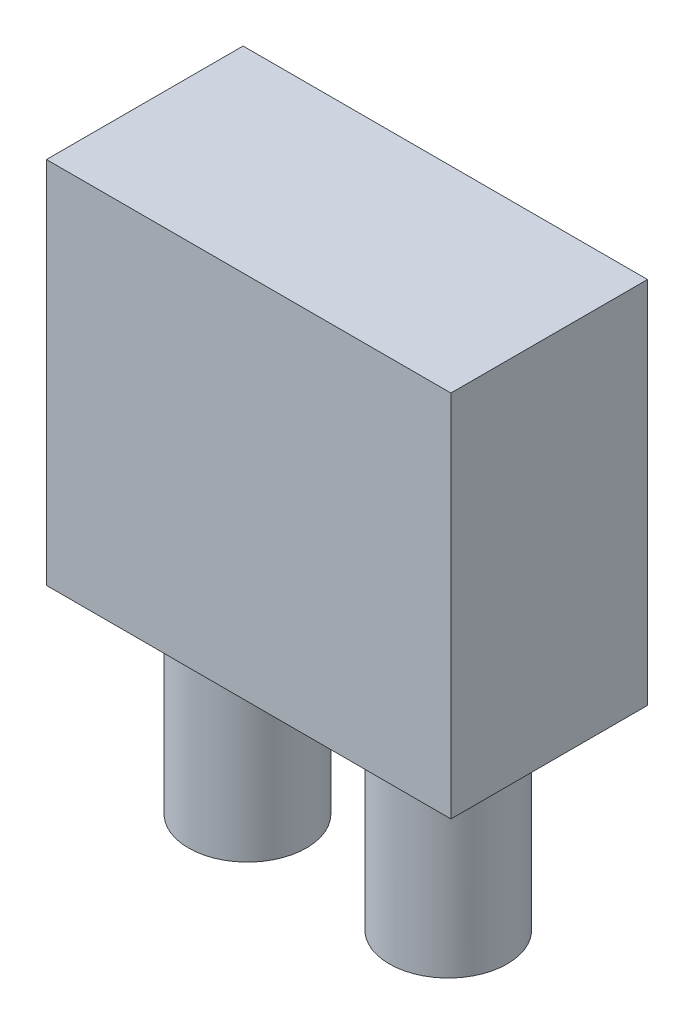
SolidWorks part; units mm, degrees
ref_plane "前视基准面" through (0, 0, 0) normal (0, 0, 1) x (1, 0, 0)
ref_plane "上视基准面" through (0, 0, 0) normal (0, 1, 0) x (1, 0, 0)
ref_plane "右视基准面" through (0, 0, 0) normal (1, 0, 0) x (0, 0, -1)
sketch "草图1" plane through (0, 0, 0) normal (0, 0, 1) x (1, 0, 0)
  line L1 (5.1425, -4.6902) -> (-5.1425, -4.6902)
  line L2 (5.1425, -4.6902) -> (5.1425, 4.6902)
  line L3 (5.1425, 4.6902) -> (-5.1425, 4.6902)
  line L4 (-5.1425, -4.6902) -> (-5.1425, 4.6902)
  line L5 (5.1425, -4.6902) -> (-5.1425, 4.6902) construction
  line L6 (5.1425, 4.6902) -> (-5.1425, -4.6902) construction
  point P0 (0, 0)
extrude "凸台-拉伸1" add sketch "草图1" along normal blind 5
sketch "草图2" plane through (0, -4.6902, 0) normal (0, -1, 0) x (1, 0, 0)
  line L0 (0, 6.6367) -> (0, -2.1332) construction
  circle A0 centre (2.5532, 2.4781) radius 1.5
  circle A1 centre (-2.5532, 2.4781) radius 1.5
extrude "凸台-拉伸2" add sketch "草图2" along normal blind 5
